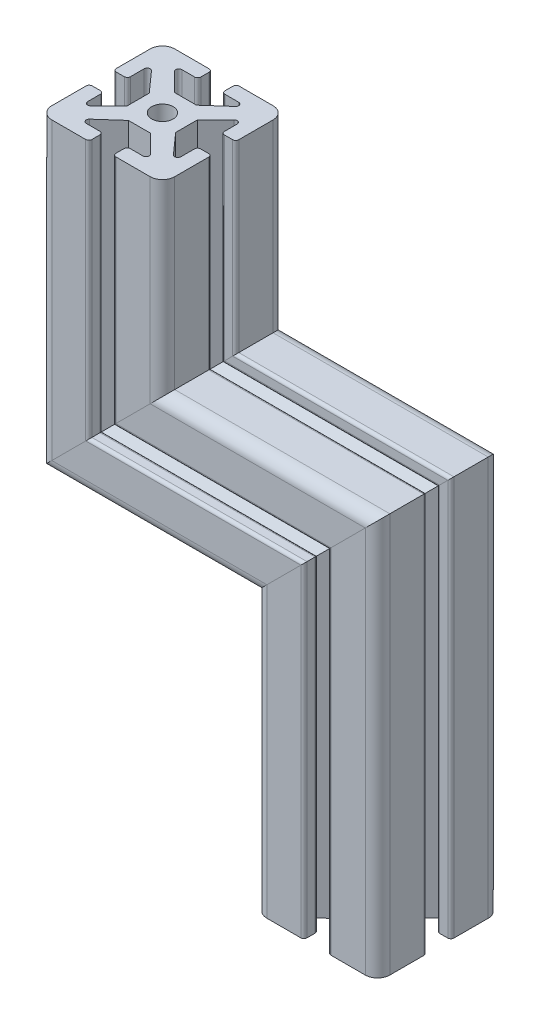
SolidWorks part; units mm, degrees
ref_plane "Front Plane" through (0, 0, 0) normal (0, 0, 1) x (1, 0, 0)
ref_plane "Top Plane" through (0, 0, 0) normal (0, 1, 0) x (1, 0, 0)
ref_plane "Right Plane" through (0, 0, 0) normal (1, 0, 0) x (0, 0, -1)
sketch3d "3DSketch2"
  line L0 (0, 0, 0) -> (0, -80, 0)
  line L1 (0, -80, 0) -> (70, -80, 0)
  line L2 (70, -80, 0) -> (70, -190, 0)
  dimension "D1" = 110
  dimension "D2" = 70
  dimension "D3" = 80
other "001 40-40_EXTRUSION(1)"
ref_plane "Plane1" through (0, 0, 0) normal (0, -1, 0) x (1, 0, 0)
sketch "Sketch1" plane through (0, 0, 0) normal (0, -1, 0) x (1, 0, 0)
  line L0 (-20, 20) -> (20, -20) construction
  line L1 (-20, -20) -> (20, -20) construction
  line L2 (-20, -20) -> (-20, 20) construction
  line L3 (-20, 20) -> (20, 20) construction
  line L4 (20, -20) -> (20, 20) construction
  line L5 (-20, -20) -> (20, 20) construction
  line L6 (-0.5117, 7.6847) -> (3.7499, 7.6847)
  line L7 (3.7499, 7.6847) -> (9.6997, 13.625)
  line L8 (8.9931, 15.3327) -> (4.8456, 15.3327)
  line L9 (3.8456, 16.3327) -> (3.8456, 19)
  line L10 (4.8456, 20) -> (16, 20)
  line L11 (20, 16) -> (20, 4.9611)
  line L12 (19, 3.9611) -> (16.3883, 3.9611)
  line L13 (15.3883, 4.9611) -> (15.3883, 9.4086)
  line L14 (13.6417, 10.0739) -> (7.6847, 3.3888)
  line L15 (7.6847, 3.3888) -> (7.6847, 0.5117)
  line L16 (7.6847, -3.7499) -> (13.625, -9.6997)
  line L17 (10.0739, -13.6417) -> (3.3888, -7.6847)
  line L18 (7.6847, 0.5117) -> (7.6847, -3.7499)
  line L19 (15.3327, -8.9931) -> (15.3327, -4.8456)
  line L20 (16.3327, -3.8456) -> (19, -3.8456)
  line L21 (20, -4.8456) -> (20, -16)
  line L22 (16, -20) -> (4.9611, -20)
  line L23 (3.9611, -19) -> (3.9611, -16.3883)
  line L24 (4.9611, -15.3883) -> (9.4086, -15.3883)
  line L25 (3.3888, -7.6847) -> (0.5117, -7.6847)
  line L26 (-3.7499, -7.6847) -> (-9.6997, -13.625)
  line L27 (-13.6417, -10.0739) -> (-7.6847, -3.3888)
  line L28 (0.5117, -7.6847) -> (-3.7499, -7.6847)
  line L29 (-8.9931, -15.3327) -> (-4.8456, -15.3327)
  line L30 (-3.8456, -16.3327) -> (-3.8456, -19)
  line L31 (-4.8456, -20) -> (-16, -20)
  line L32 (-20, -16) -> (-20, -4.9611)
  line L33 (-19, -3.9611) -> (-16.3883, -3.9611)
  line L34 (-15.3883, -4.9611) -> (-15.3883, -9.4086)
  line L35 (-7.6847, -3.3888) -> (-7.6847, -0.5117)
  line L36 (-7.6847, 3.7499) -> (-13.625, 9.6997)
  line L37 (-10.0739, 13.6417) -> (-3.3888, 7.6847)
  line L38 (-7.6847, -0.5117) -> (-7.6847, 3.7499)
  line L39 (-15.3327, 8.9931) -> (-15.3327, 4.8456)
  line L40 (-16.3327, 3.8456) -> (-19, 3.8456)
  line L41 (-20, 4.8456) -> (-20, 16)
  line L42 (-16, 20) -> (-4.9611, 20)
  line L43 (-3.9611, 19) -> (-3.9611, 16.3883)
  line L44 (-4.9611, 15.3883) -> (-9.4086, 15.3883)
  line L45 (-3.3888, 7.6847) -> (-0.5117, 7.6847)
  circle A0 centre (0, 0) radius 3.4925
  arc A1 (20, 4.9611) -> (19, 3.9611) centre (19, 4.9611) cw
  arc A2 (16.3883, 3.9611) -> (15.3883, 4.9611) centre (16.3883, 4.9611) cw
  arc A3 (4.8456, 15.3327) -> (3.8456, 16.3327) centre (4.8456, 16.3327) cw
  arc A4 (3.8456, 19) -> (4.8456, 20) centre (4.8456, 19) cw
  arc A5 (9.6997, 13.625) -> (8.9931, 15.3327) centre (8.9931, 14.3327) ccw
  arc A6 (15.3883, 9.4086) -> (13.6417, 10.0739) centre (14.3883, 9.4086) ccw
  arc A7 (20, 16) -> (16, 20) centre (16, 16) ccw
  arc A8 (15.3327, -4.8456) -> (16.3327, -3.8456) centre (16.3327, -4.8456) cw
  arc A9 (19, -3.8456) -> (20, -4.8456) centre (19, -4.8456) cw
  arc A10 (16, -20) -> (20, -16) centre (16, -16) ccw
  arc A11 (4.9611, -20) -> (3.9611, -19) centre (4.9611, -19) cw
  arc A12 (3.9611, -16.3883) -> (4.9611, -15.3883) centre (4.9611, -16.3883) cw
  arc A13 (9.4086, -15.3883) -> (10.0739, -13.6417) centre (9.4086, -14.3883) ccw
  arc A14 (13.625, -9.6997) -> (15.3327, -8.9931) centre (14.3327, -8.9931) ccw
  arc A15 (-4.8456, -15.3327) -> (-3.8456, -16.3327) centre (-4.8456, -16.3327) cw
  arc A16 (-3.8456, -19) -> (-4.8456, -20) centre (-4.8456, -19) cw
  arc A17 (-20, -16) -> (-16, -20) centre (-16, -16) ccw
  arc A18 (-20, -4.9611) -> (-19, -3.9611) centre (-19, -4.9611) cw
  arc A19 (-16.3883, -3.9611) -> (-15.3883, -4.9611) centre (-16.3883, -4.9611) cw
  arc A20 (-15.3883, -9.4086) -> (-13.6417, -10.0739) centre (-14.3883, -9.4086) ccw
  arc A21 (-9.6997, -13.625) -> (-8.9931, -15.3327) centre (-8.9931, -14.3327) ccw
  arc A22 (-15.3327, 4.8456) -> (-16.3327, 3.8456) centre (-16.3327, 4.8456) cw
  arc A23 (-19, 3.8456) -> (-20, 4.8456) centre (-19, 4.8456) cw
  arc A24 (-16, 20) -> (-20, 16) centre (-16, 16) ccw
  arc A25 (-4.9611, 20) -> (-3.9611, 19) centre (-4.9611, 19) cw
  arc A26 (-3.9611, 16.3883) -> (-4.9611, 15.3883) centre (-4.9611, 16.3883) cw
  arc A27 (-9.4086, 15.3883) -> (-10.0739, 13.6417) centre (-9.4086, 14.3883) ccw
  arc A28 (-13.625, 9.6997) -> (-15.3327, 8.9931) centre (-14.3327, 8.9931) ccw
  point P103 (0, 0)
  dimension "D3" = 1
  dimension "D4" = 4
  dimension "D1" = 40
  dimension "D2" = 40
